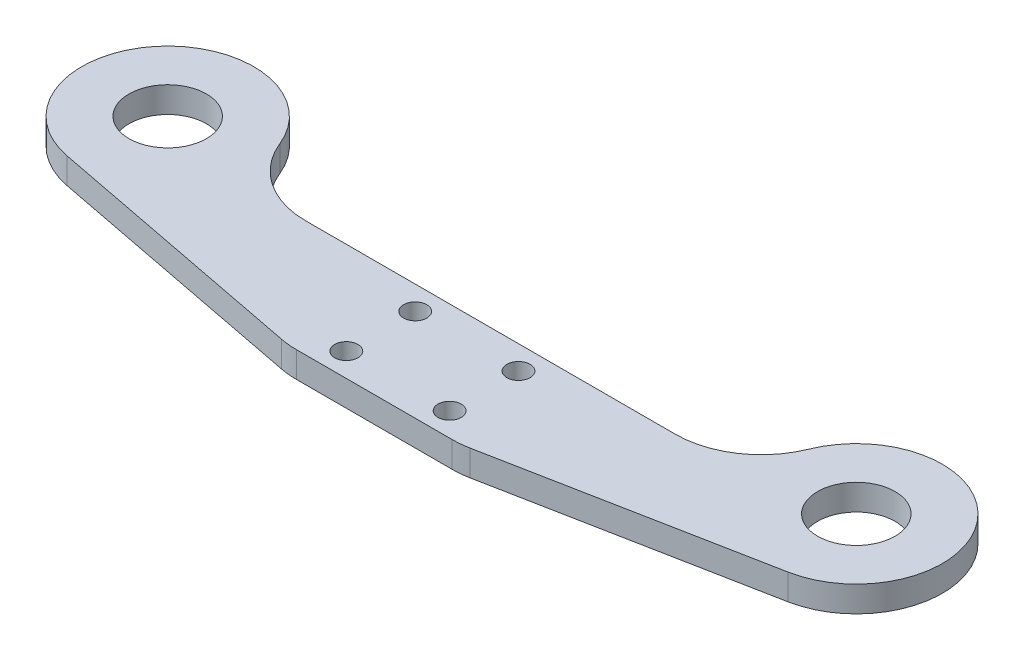
SolidWorks part; units mm, degrees
material "Thornel Mat VMA"
ref_plane "前视基准面" through (0, 0, 0) normal (0, 0, 1) x (1, 0, 0)
ref_plane "上视基准面" through (0, 0, 0) normal (0, 1, 0) x (1, 0, 0)
ref_plane "右视基准面" through (0, 0, 0) normal (1, 0, 0) x (0, 0, -1)
sketch "草图1" plane through (0, 0, 0) normal (0, 1, 0) x (1, 0, 0)
  line L0 (0, 96.7451) -> (0, -124.7987) construction
  line L1 (-10, 6.75) -> (10, 6.75)
  line L2 (-10, 6.75) -> (-10, -6.75)
  line L3 (-10, -6.75) -> (10, -6.75)
  line L4 (10, 6.75) -> (10, -6.75)
  line L5 (-10, 6.75) -> (10, -6.75) construction
  line L6 (-10, -6.75) -> (10, 6.75) construction
  line L7 (10, -6.75) -> (46, -6.75)
  line L8 (-10, 6.75) -> (-46, 6.75)
  line L9 (-10, 6.75) -> (-10, -6.75)
  line L10 (-10, -6.75) -> (-46, -6.75)
  line L11 (-46, 6.75) -> (-46, -6.75)
  line L14 (-6, 4) -> (6, 4) construction
  line L15 (-6, 4) -> (-6, -4) construction
  line L16 (-6, -4) -> (6, -4) construction
  line L17 (6, 4) -> (6, -4) construction
  line L18 (-6, 4) -> (6, -4) construction
  line L19 (-6, -4) -> (6, 4) construction
  line L22 (46, 6.75) -> (46, -6.75)
  line L23 (10, 6.75) -> (46, 6.75)
  line L24 (10, 6.75) -> (10, -6.75)
  line L25 (-10, 6.75) -> (-30.3175, 6.75)
  line L30 (-10, -6.75) -> (-41.9026, -0.5673)
  line L31 (46, 6.75) -> (10, 6.75)
  line L32 (10, -6.75) -> (41.9026, -0.5673)
  circle A0 centre (-40, 9.25) radius 4.5
  circle A1 centre (40, 9.25) radius 4.5
  circle A2 centre (-6, 4) radius 1.35
  circle A3 centre (-6, -4) radius 1.35
  circle A4 centre (6, -4) radius 1.35
  circle A5 centre (6, 4) radius 1.35
  circle A6 centre (-40, 9.25) radius 10
  circle A7 centre (40, 9.25) radius 10
  point P0 (0, 0)
  point P15 (0, 0)
  dimension "D3" = 9
  dimension "D10" = 2.7
  dimension "D11" = 2.7
  dimension "D12" = 2.7
  dimension "D13" = 2.7
  dimension "D7" = 20
  dimension "D1" = 13.5
  dimension "D2" = 20
  dimension "D4" = 16
  dimension "D5" = 40
  dimension "D8" = 8
  dimension "D9" = 12
extrude "凸台-拉伸1" add sketch "草图1" along normal blind 3
fillet "圆角1" radius 10 2 edges at (30.3175, 1.5, -6.75) (-30.3175, 1.5, -6.75)
fillet "圆角2" radius 10 2 edges at (10, 1.5, 6.75) (-10, 1.5, 6.75)
